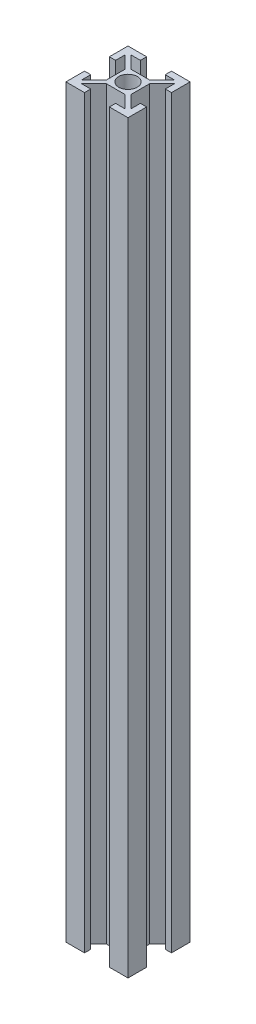
SolidWorks part; units mm, degrees
material "1060 Alloy"
ref_plane "Front Plane" through (0, 0, 0) normal (0, 0, 1) x (1, 0, 0)
ref_plane "Top Plane" through (0, 0, 0) normal (0, 1, 0) x (1, 0, 0)
ref_plane "Right Plane" through (0, 0, 0) normal (1, 0, 0) x (0, 0, -1)
sketch "2020 sketch" plane through (0, 0, 0) normal (0, 1, 0) x (1, 0, 0)
  line L0 (-4, 10) -> (-4, 8)
  line L1 (-10, 10) -> (-4, 10)
  line L2 (-10, 10) -> (-10, 4)
  line L3 (-10, -10) -> (-4, -10)
  line L4 (10, 10) -> (10, 4)
  line L5 (-10, 10) -> (10, -10) construction
  line L6 (-10, -10) -> (10, 10) construction
  line L7 (-4, 8) -> (-7, 8)
  line L8 (-7, 8) -> (-3, 4)
  line L9 (-3, 4) -> (3, 4)
  line L10 (3, 4) -> (7, 8)
  line L11 (7, 8) -> (4, 8)
  line L12 (4, 8) -> (4, 10)
  line L13 (4, 3) -> (4, -3)
  line L14 (8, 7) -> (4, 3)
  line L15 (8, 4) -> (8, 7)
  line L16 (10, 4) -> (8, 4)
  line L17 (8, -4) -> (10, -4)
  line L18 (8, -7) -> (8, -4)
  line L19 (4, -3) -> (8, -7)
  line L20 (3, -4) -> (-3, -4)
  line L21 (7, -8) -> (3, -4)
  line L22 (4, -8) -> (7, -8)
  line L23 (4, -10) -> (4, -8)
  line L24 (-4, -8) -> (-4, -10)
  line L25 (-7, -8) -> (-4, -8)
  line L26 (-3, -4) -> (-7, -8)
  line L27 (-4, -3) -> (-4, 3)
  line L28 (-8, -7) -> (-4, -3)
  line L29 (-8, -4) -> (-8, -7)
  line L30 (-10, -4) -> (-8, -4)
  line L31 (-8, 4) -> (-10, 4)
  line L32 (-8, 7) -> (-8, 4)
  line L33 (-4, 3) -> (-8, 7)
  line L34 (-10, -4) -> (-10, -10)
  line L35 (10, -4) -> (10, -10)
  line L36 (4, 10) -> (10, 10)
  line L37 (4, -10) -> (10, -10)
  circle A0 centre (0, 0) radius 3
  point P0 (0, 0)
  point P14 (4, 9)
  point P42 (0, 0)
  dimension "D9" = 6
  dimension "D1" = 20
  dimension "D2" = 20
  dimension "D3" = 8
  dimension "D4" = 6
  dimension "D5" = 6
  dimension "D6" = 2
  dimension "D7" = 4
  dimension "D8" = 4
extrude "Boss-Extrude1" add sketch "2020 sketch" along normal blind 240 contours A0 | L28 L27 L33 L32 L31 L2 L1 L0 L7 L8 L9 L10 L11 L12 L36 L4 L16 L15 L14 L13 L19 L18 L17 L35 L37 L23 L22 L21 L20 L26 L25 L24 L3 L34 L30 L29
